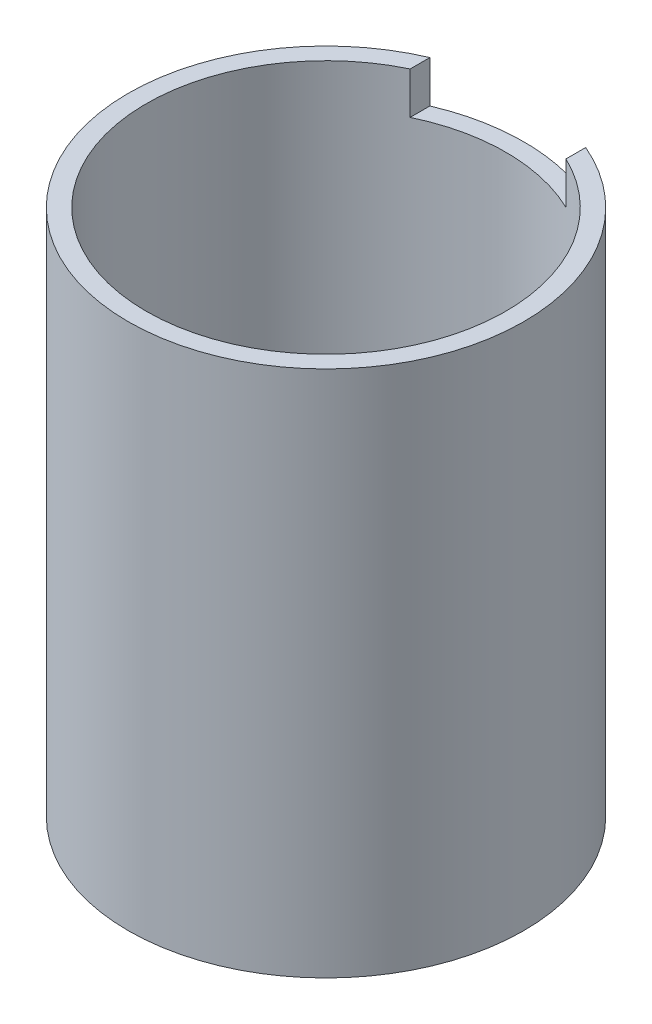
SolidWorks part; units mm, degrees
ref_plane "Front Plane" through (0, 0, 0) normal (0, 0, 1) x (1, 0, 0)
ref_plane "Top Plane" through (0, 0, 0) normal (0, 1, 0) x (1, 0, 0)
ref_plane "Right Plane" through (0, 0, 0) normal (1, 0, 0) x (0, 0, -1)
sketch "Sketch1" plane through (0, 0, 0) normal (0, 1, 0) x (1, 0, 0)
  circle A0 centre (0, 0) radius 16.5
  circle A1 centre (0, 0) radius 15
  dimension "D1" = 30
  dimension "D2" = 33
extrude "Boss-Extrude1" add sketch "Sketch1" along normal blind 44
sketch "Sketch3" plane through (0, 0, 0) normal (0, 0, 1) x (1, 0, 0)
  line L0 (-16.5, 0) -> (16.5, 0) construction
  line L1 (-6.5, 3.5) -> (6.5, 3.5)
  line L2 (-6.5, 3.5) -> (-6.5, 0)
  line L3 (-6.5, 0) -> (6.5, 0)
  line L4 (6.5, 3.5) -> (6.5, 0)
  line L12 (6.5, 40.5) -> (6.5, 44)
  line L13 (-6.5, 44) -> (6.5, 44)
  line L14 (-6.5, 40.5) -> (-6.5, 44)
  line L15 (-6.5, 40.5) -> (6.5, 40.5)
  point P0 (0, 1.75)
  point P18 (0, 42.25)
  dimension "D1" = 6.5
  dimension "D2" = 1.75
  dimension "D3" = 3.5
  dimension "D4" = 40.5
  dimension "D5" = 42.25
extrude "Cut-Extrude1" cut sketch "Sketch3" against normal blind 44
